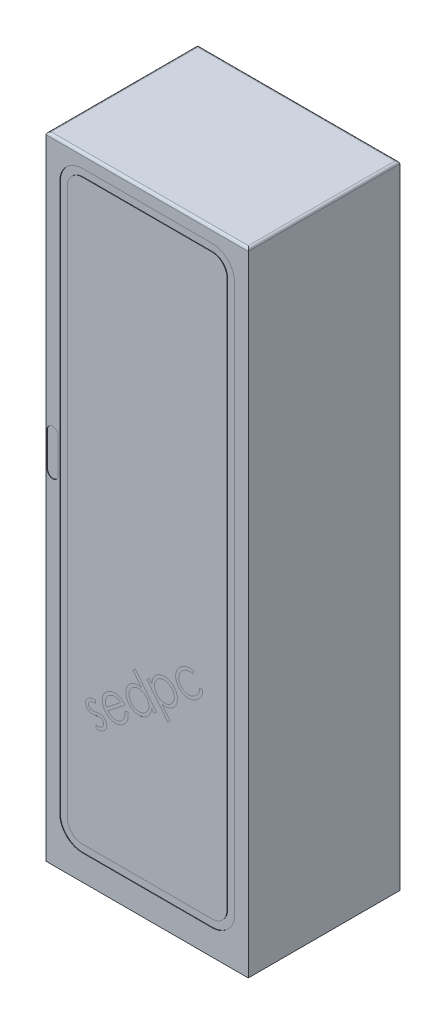
SolidWorks part; units mm, degrees
ref_plane "Alzado" through (0, 0, 0) normal (0, 0, 1) x (1, 0, 0)
ref_plane "Planta" through (0, 0, 0) normal (0, 1, 0) x (1, 0, 0)
ref_plane "Vista lateral" through (0, 0, 0) normal (1, 0, 0) x (0, 0, -1)
sketch "Croquis1" plane through (0, 0, 0) normal (0, 1, 0) x (1, 0, 0)
  line L1 (-400, 300) -> (400, 300)
  line L2 (-400, 300) -> (-400, -300)
  line L3 (-400, -300) -> (400, -300)
  line L4 (400, 300) -> (400, -300)
  line L5 (-400, 300) -> (400, -300) construction
  line L6 (-400, -300) -> (400, 300) construction
  point P0 (0, 0)
  dimension "D1" = 800
  dimension "D2" = 600
extrude "Saliente-Extruir1" add sketch "Croquis1" along normal blind 2500
sketch "Croquis2" plane through (0, 0, 300) normal (0, 0, 1) x (1, 0, 0)
  line L0 (-345.9954, 2356.5495) -> (-345.9954, 190.8498)
  line L1 (-255.9954, 2416.5495) -> (255.9954, 2416.5495)
  line L2 (-315.9954, 2356.5495) -> (-315.9954, 190.8498)
  line L3 (-255.9954, 130.8498) -> (255.9954, 130.8498)
  line L4 (315.9954, 2356.5495) -> (315.9954, 190.8498)
  line L5 (-315.9954, 2416.5495) -> (315.9954, 130.8498) construction
  line L6 (-315.9954, 130.8498) -> (315.9954, 2416.5495) construction
  line L7 (-255.9954, 100.8498) -> (255.9954, 100.8498)
  line L8 (345.9954, 2356.5495) -> (345.9954, 190.8498)
  line L9 (-255.9954, 2446.5495) -> (255.9954, 2446.5495)
  arc A0 (-315.9954, 190.8498) -> (-255.9954, 130.8498) centre (-255.9954, 190.8498) ccw
  arc A1 (255.9954, 130.8498) -> (315.9954, 190.8498) centre (255.9954, 190.8498) ccw
  arc A2 (255.9954, 2416.5495) -> (315.9954, 2356.5495) centre (255.9954, 2356.5495) cw
  arc A3 (-255.9954, 2416.5495) -> (-315.9954, 2356.5495) centre (-255.9954, 2356.5495) ccw
  arc A4 (-345.9954, 190.8498) -> (-255.9954, 100.8498) centre (-255.9954, 190.8498) ccw
  arc A5 (255.9954, 100.8498) -> (345.9954, 190.8498) centre (255.9954, 190.8498) ccw
  arc A6 (255.9954, 2446.5495) -> (345.9954, 2356.5495) centre (255.9954, 2356.5495) cw
  arc A7 (-255.9954, 2446.5495) -> (-345.9954, 2356.5495) centre (-255.9954, 2356.5495) ccw
  point P0 (0, 1273.6997)
  dimension "D1" = 60
  dimension "D2" = 30
extrude "Cortar-Extruir1" cut sketch "Croquis2" against normal blind 2
sketch "Croquis3" plane through (0, 0, 300) normal (0, 0, 1) x (1, 0, 0)
  line L0 (-374.0328, 1482.1163) -> (-374.0328, 1345.9345) construction
  line L1 (-352.0396, 1482.1163) -> (-352.0396, 1345.9345)
  line L2 (-396.0259, 1482.1163) -> (-396.0259, 1345.9345)
  arc A0 (-352.0396, 1482.1163) -> (-396.0259, 1482.1163) centre (-374.0328, 1482.1163) ccw
  arc A1 (-396.0259, 1345.9345) -> (-352.0396, 1345.9345) centre (-374.0328, 1345.9345) ccw
  point P2 (-374.0328, 1414.0254)
extrude "Cortar-Extruir2" cut sketch "Croquis3" against normal blind 2
sketch "Croquis4" plane through (0, 0, 300) normal (0, 0, 1) x (1, 0, 0)
  line L0 (-315.9954, 450) -> (315.9954, 950) construction
  line L2 (-315.9954, 2356.5495) -> (-315.9954, 190.8498) construction
  line L3 (-315.9954, 450) -> (-315.9954, 0) construction
  line L4 (-400, 0) -> (400, 0) construction
  line L5 (315.9954, 190.8498) -> (315.9954, 2356.5495) construction
  line L7 (-315.9954, 2356.5495) -> (-315.9954, 190.8498) construction
  text T0 " sedpc" font "Century Gothic" height in points 500
  dimension "D1" = 450
  dimension "D2" = 950
extrude "Cortar-Extruir3" cut sketch "Croquis4" against normal blind 0.001
fillet "Redondeo1" radius 10 4 edges at (0, 2500, -300) (-400, 2500, 0) (400, 2500, 0) (0, 2500, 300)
sketch "Croquis5" plane through (0, 0, 0) normal (0, -1, 0) x (1, 0, 0)
  line L0 (-375.2044, -274.2799) -> (-375.2044, 274.2799)
  line L1 (-385.2044, -284.2799) -> (385.2044, -284.2799)
  line L2 (-385.2044, -284.2799) -> (-385.2044, 284.2799)
  line L3 (-385.2044, 284.2799) -> (385.2044, 284.2799)
  line L4 (385.2044, -284.2799) -> (385.2044, 284.2799)
  line L5 (-385.2044, -284.2799) -> (385.2044, 284.2799) construction
  line L6 (-385.2044, 284.2799) -> (385.2044, -284.2799) construction
  line L7 (-375.2044, 274.2799) -> (375.2044, 274.2799)
  line L8 (375.2044, -274.2799) -> (375.2044, 274.2799)
  line L9 (-375.2044, -274.2799) -> (375.2044, -274.2799)
  point P0 (0, 0)
  dimension "D1" = 10
extrude "Cortar-Extruir4" cut sketch "Croquis5" against normal blind 10
